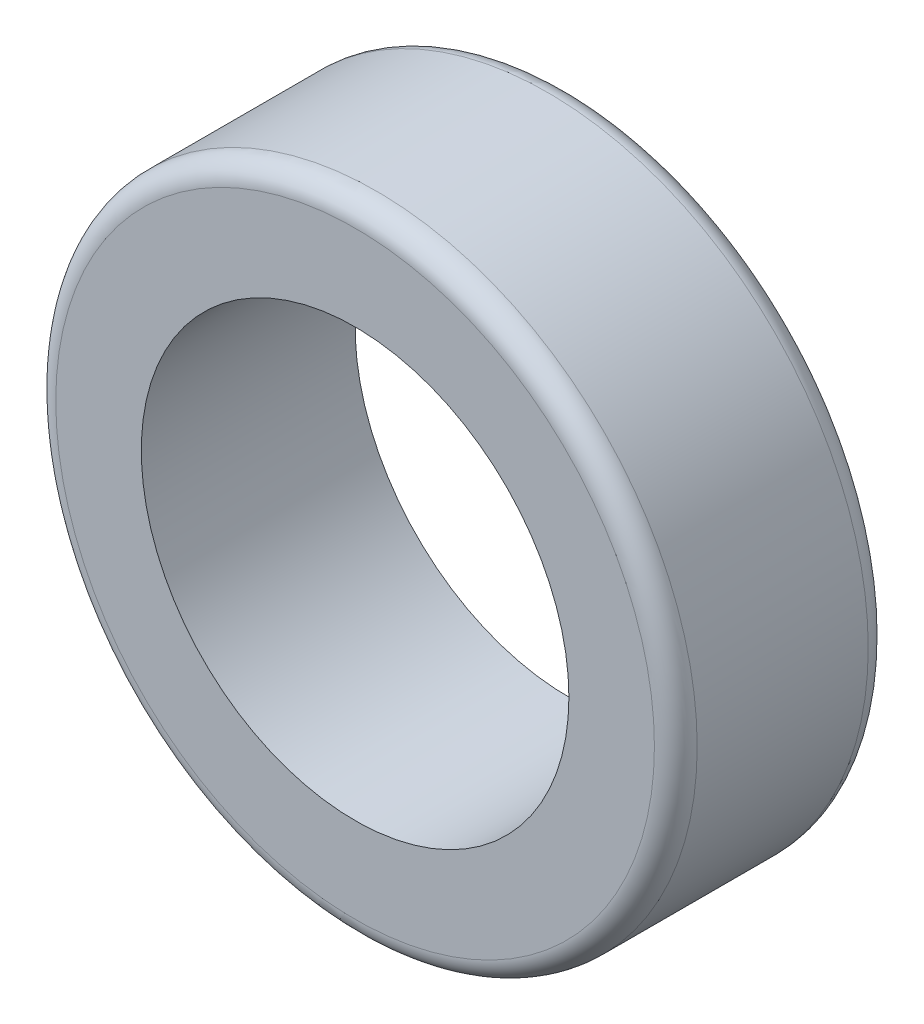
SolidWorks part; units mm, degrees
ref_plane "Front Plane" through (0, 0, 0) normal (0, 0, 1) x (1, 0, 0)
ref_plane "Top Plane" through (0, 0, 0) normal (0, 1, 0) x (1, 0, 0)
ref_plane "Right Plane" through (0, 0, 0) normal (1, 0, 0) x (0, 0, -1)
sketch "Sketch1" plane through (0, 0, 0) normal (0, 0, 1) x (1, 0, 0)
  circle A0 centre (0, 0) radius 1
  circle A1 centre (0, 0) radius 1.5
  dimension "D1" = 2
  dimension "D2" = 3
extrude "Boss-Extrude1" add sketch "Sketch1" along normal blind 1
fillet "Fillet1" radius 0.1 2 edges at (1.5, 0, 0) (1.5, 0, 1)
